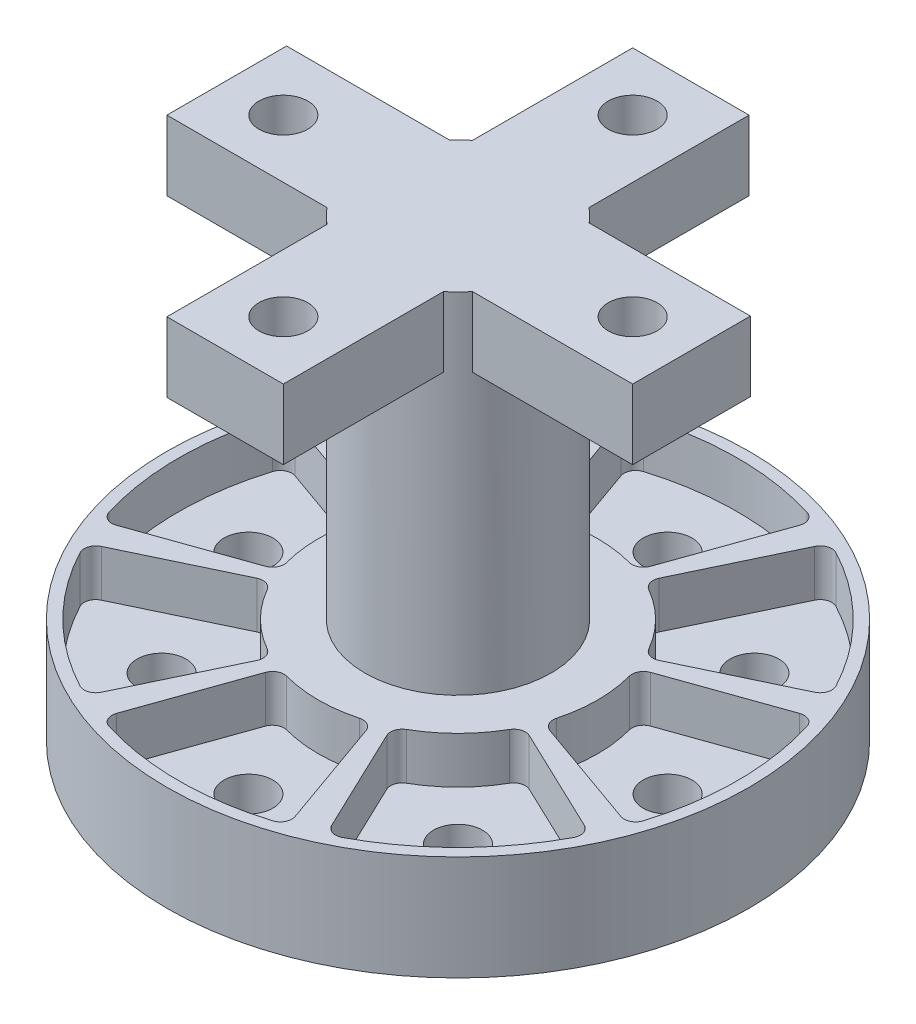
SolidWorks part; units mm, degrees
ref_plane "Спереди" through (0, 0, 0) normal (0, 0, 1) x (1, 0, 0)
ref_plane "Сверху" through (0, 0, 0) normal (0, 1, 0) x (1, 0, 0)
ref_plane "Справа" through (0, 0, 0) normal (1, 0, 0) x (0, 0, -1)
sketch "Эскиз1" plane through (0, 0, 0) normal (0, 1, 0) x (1, 0, 0)
  circle A1 centre (-18, 0) radius 2.1
  circle A2 centre (-12.7279, 12.7279) radius 2.1
  circle A3 centre (0, 18) radius 2.1
  circle A4 centre (12.7279, 12.7279) radius 2.1
  circle A5 centre (18, 0) radius 2.1
  circle A6 centre (12.7279, -12.7279) radius 2.1
  circle A7 centre (0, -18) radius 2.1
  circle A8 centre (-12.7279, -12.7279) radius 2.1
  circle A9 centre (0, 0) radius 25
extrude "Бобышка-Вытянуть1" add sketch "Эскиз1" along normal blind 5
ref_plane "Плоскость1" through (0, 5, 0) normal (0, 1, 0) x (1, 0, 0)
sketch "Эскиз2" plane through (0, 5, 0) normal (0, 1, 0) x (1, 0, 0)
  line L32 (-5.1661, -10.831) -> (-10.3323, -21.662)
  line L33 (-4.0057, -11.3117) -> (-8.0114, -22.6234)
  line L34 (-10.831, -5.1661) -> (-21.662, -10.3323)
  line L35 (-22.6234, -8.0114) -> (-11.3117, -4.0057)
  line L36 (-11.3117, 4.0057) -> (-22.6234, 8.0114)
  line L37 (-21.662, 10.3323) -> (-10.831, 5.1661)
  line L38 (-10.3323, 21.662) -> (-5.1661, 10.831)
  line L39 (-8.0114, 22.6234) -> (-4.0057, 11.3117)
  line L40 (8.0114, 22.6234) -> (4.0057, 11.3117)
  line L41 (10.3323, 21.662) -> (5.1661, 10.831)
  line L42 (10.831, 5.1661) -> (21.662, 10.3323)
  line L43 (11.3117, 4.0057) -> (22.6234, 8.0114)
  line L44 (11.3117, -4.0057) -> (22.6234, -8.0114)
  line L45 (10.831, -5.1661) -> (21.662, -10.3323)
  line L46 (5.1661, -10.831) -> (10.3323, -21.662)
  line L47 (4.0057, -11.3117) -> (8.0114, -22.6234)
  circle A1 centre (0, 0) radius 12
  circle A2 centre (0, 0) radius 25
  circle A4 centre (0, 0) radius 24
extrude "Бобышка-Вытянуть2" add sketch "Эскиз2" along normal blind 4 contours A2 A4 | A1 | L39 A4 L38 A1 | L41 A4 L40 A1 | L43 A4 L42 A1 | L45 A4 L44 A1 | L47 A4 L46 A1 | L32 A4 L33 A1 | L35 A4 L34 A1 | L37 A4 L36 A1
fillet "Скругление1" radius 1 32 edges at (-4.0057, 7, -11.3117) (4.0057, 7, -11.3117) (8.0114, 7, -22.6234) (-8.0114, 7, -22.6234) (21.662, 7, -10.3323) (10.3323, 7, -21.662) (5.1661, 7, -10.831) (10.831, 7, -5.1661) (22.6234, 7, -8.0114) (11.3117, 7, -4.0057) (11.3117, 7, 4.0057) (22.6234, 7, 8.0114) (21.662, 7, 10.3323) (10.831, 7, 5.1661) (5.1661, 7, 10.831) (10.3323, 7, 21.662) (8.0114, 7, 22.6234) (4.0057, 7, 11.3117) (-4.0057, 7, 11.3117) (-8.0114, 7, 22.6234) (-10.3323, 7, 21.662) (-5.1661, 7, 10.831) (-10.831, 7, 5.1661) (-21.662, 7, 10.3323) (-11.3117, 7, 4.0057) (-11.3117, 7, -4.0057) (-22.6234, 7, 8.0114) (-22.6234, 7, -8.0114) (-10.831, 7, -5.1661) (-5.1661, 7, -10.831) (-21.662, 7, -10.3323) (-10.3323, 7, -21.662)
ref_plane "Плоскость2" through (0, 9, 0) normal (0, 1, 0) x (1, 0, 0)
sketch "Эскиз3" plane through (0, 9, 0) normal (0, 1, 0) x (1, 0, 0)
  circle A0 centre (0, 0) radius 8
extrude "Бобышка-Вытянуть3" add sketch "Эскиз3" along normal blind 30
ref_plane "Плоскость3" through (0, 39, 0) normal (0, 1, 0) x (1, 0, 0)
sketch "Эскиз4" plane through (0, 39, 0) normal (0, 1, 0) x (1, 0, 0)
  line L4 (5, -20) -> (5, -5)
  line L5 (-20, -5) -> (-20, 5.2806)
  line L6 (-5, 20) -> (5, 20)
  line L7 (20, -5) -> (20, 5.1101)
  line L10 (-20, 5.2806) -> (-5, 5.2806)
  line L13 (5, 20) -> (5, 5.1101)
  line L15 (-5, 5.2806) -> (-5, 20)
  line L17 (5, -5) -> (20, -5)
  line L27 (5, -20) -> (-5, -20)
  line L28 (-5, -20) -> (-5, -5)
  line L29 (-20, -5) -> (-5, -5)
  line L32 (5, 5.1101) -> (20, 5.1101)
  circle A0 centre (15, 0) radius 2.1
  circle A1 centre (0, 15) radius 2.1
  circle A6 centre (-15, 0) radius 2.1
  circle A7 centre (0, -15) radius 2.1
extrude "Бобышка-Вытянуть5" add sketch "Эскиз4" against normal blind 6
